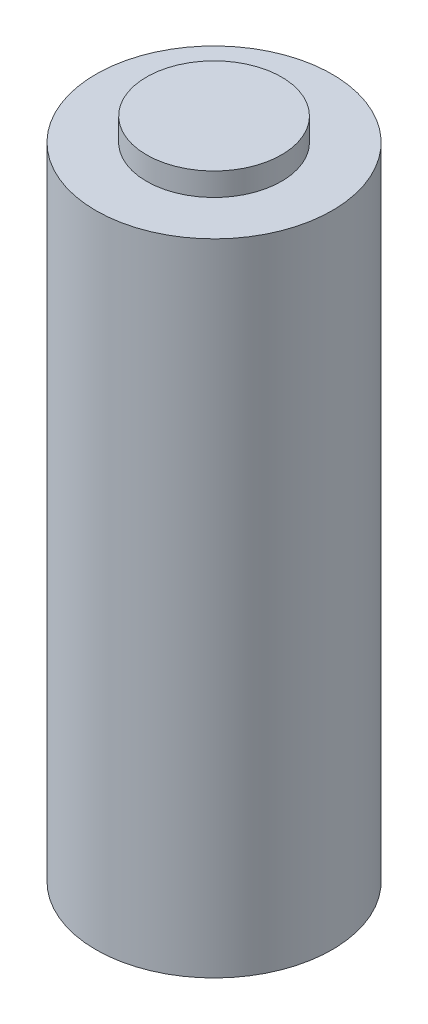
SolidWorks part; units mm, degrees
ref_plane "Alzado" through (0, 0, 0) normal (0, 0, 1) x (1, 0, 0)
ref_plane "Planta" through (0, 0, 0) normal (0, 1, 0) x (1, 0, 0)
ref_plane "Vista lateral" through (0, 0, 0) normal (1, 0, 0) x (0, 0, -1)
sketch "Croquis1" plane through (0, 0, 0) normal (0, 1, 0) x (1, 0, 0)
  circle A0 centre (0, 0) radius 5.15
  dimension "D1" = 10.3
extrude "Saliente-Extruir1" add sketch "Croquis1" along normal blind 28.9
sketch "Croquis2" plane through (0, 28.9, 0) normal (0, 1, 0) x (1, 0, 0)
  circle A0 centre (0, 0) radius 2.9418
  circle A1 centre (0, 0) radius 5.15
extrude "Cortar-Extruir1" cut sketch "Croquis2" against normal blind 1
